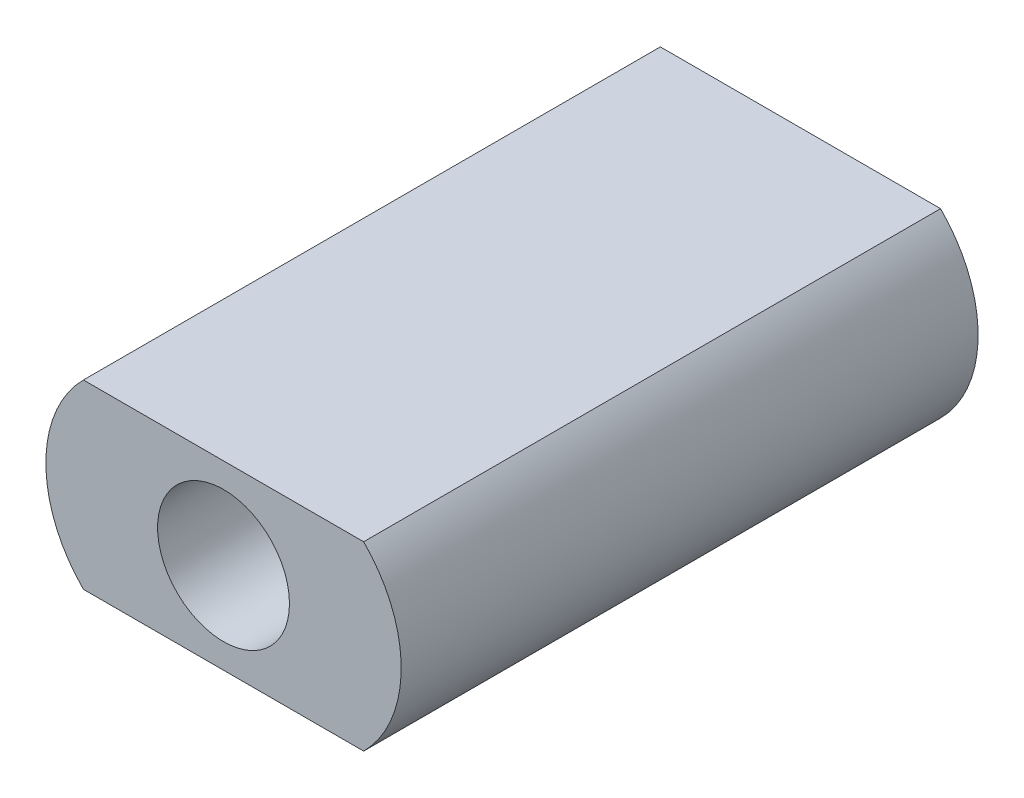
SolidWorks part; units mm, degrees
ref_plane "Alzado" through (0, 0, 0) normal (0, 0, 1) x (1, 0, 0)
ref_plane "Planta" through (0, 0, 0) normal (0, 1, 0) x (1, 0, 0)
ref_plane "Vista lateral" through (0, 0, 0) normal (1, 0, 0) x (0, 0, -1)
sketch "Croquis1" plane through (0, 0, 0) normal (0, 0, 1) x (1, 0, 0)
  line L0 (0, 8.8723) -> (0, -8.1496) construction
  line L1 (8.5, -5.5) -> (-8.5, -5.5)
  line L3 (8.5, 5.5) -> (-8.5, 5.5)
  line L5 (8.5, -5.5) -> (-8.5, 5.5) construction
  line L6 (8.5, 5.5) -> (-8.5, -5.5) construction
  arc A0 (-8.5, 5.5) -> (-8.5, -5.5) centre (-3, 0) ccw
  arc A1 (8.5, 5.5) -> (8.5, -5.5) centre (3, 0) cw
  point P0 (0, 0)
  dimension "D1" = 11
  dimension "D2" = 17
extrude "Saliente-Extruir1" add sketch "Croquis1" along normal mid plane 35
sketch "Croquis2" plane through (0, 0, 17.5) normal (0, 0, 1) x (1, 0, 0)
  circle A0 centre (0, 0) radius 4
  dimension "D1" = 8
extrude "Cortar-Extruir1" cut sketch "Croquis2" against normal blind 20
